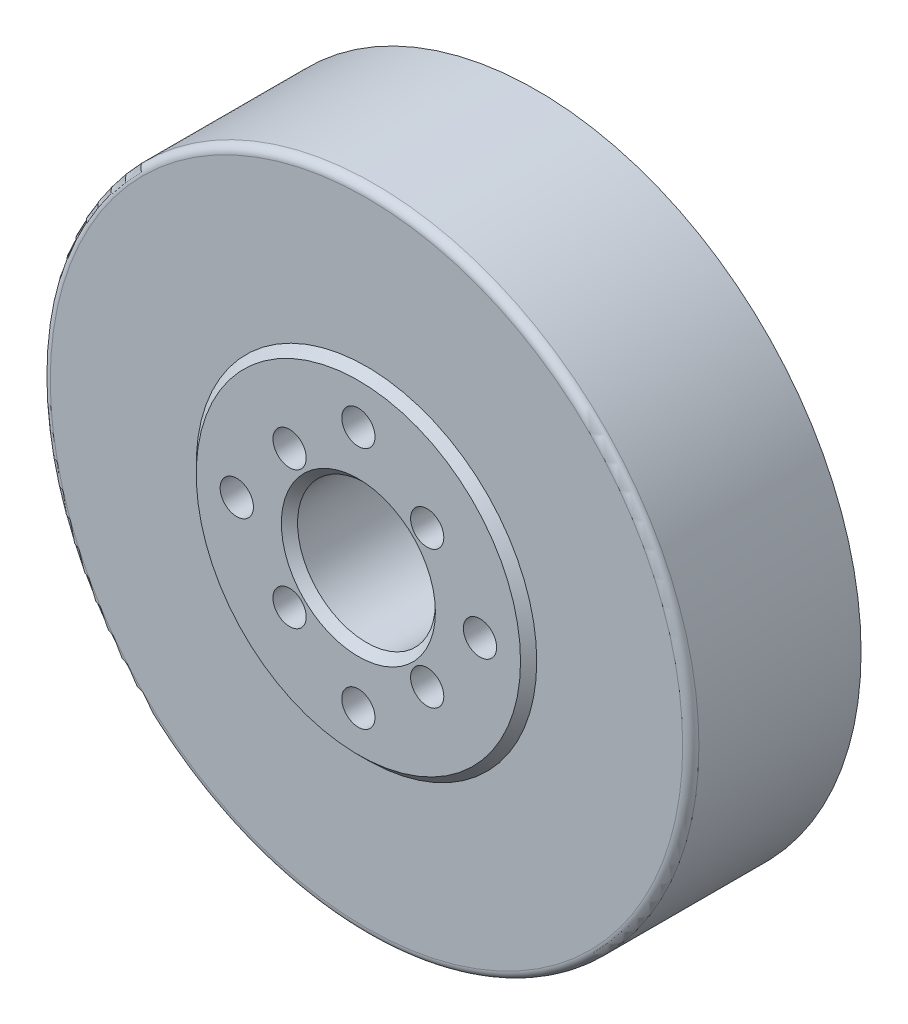
SolidWorks part; units mm, degrees
ref_plane "Front Plane" through (0, 0, 0) normal (1, 0, 0) x (0, 1, 0)
ref_plane "Top Plane" through (0, 0, 0) normal (0, 0, 1) x (0, 1, 0)
ref_plane "Right Plane" through (0, 0, 0) normal (0, 1, 0) x (-1, 0, 0)
sketch "Sketch1" plane through (0, 0, 0) normal (0, 0, 1) x (0, 1, 0)
  circle A0 centre (0, 0) radius 20
  dimension "D1" = 40
extrude "Boss-Extrude1" add sketch "Sketch1" along normal blind 10.5
sketch "Sketch2" plane through (0, 0, 10.5) normal (0, 0, 1) x (1, 0, 0)
  circle A0 centre (0, 0) radius 4.25
  circle A1 centre (0, 0) radius 10.5
  dimension "D1" = 8.5
  dimension "D2" = 21
extrude "Boss-Extrude3" add sketch "Sketch2" along normal blind 0.5 draft 45
sketch "Sketch3" plane through (0, 0, 10.5) normal (0, 0, 1) x (1, 0, 0)
  circle A0 centre (0, 0) radius 4.25
  circle A1 centre (0, 0) radius 4.25 construction
extrude "Cut-Extrude1" cut sketch "Sketch3" against normal blind 10.5
sketch "Sketch10" plane through (0, 0, 11) normal (0, 0, 1) x (0, -1, 0)
  line L1 (-7.5, 0) -> (0, -7.5) construction
  line L2 (0, -7.5) -> (7.5, 0) construction
  line L3 (7.5, 0) -> (0, 7.5) construction
  line L4 (0, 7.5) -> (-7.5, 0) construction
  line L5 (4.2426, 4.2426) -> (-4.2426, 4.2426) construction
  line L6 (-4.2426, 4.2426) -> (-4.2426, -4.2426) construction
  line L7 (-4.2426, -4.2426) -> (4.2426, -4.2426) construction
  line L8 (4.2426, -4.2426) -> (4.2426, 4.2426) construction
  circle A0 centre (0, 0) radius 7.5 construction
  circle A1 centre (0, 0) radius 6 construction
  point P2 (-7.5, 0)
  point P3 (0, -7.5)
  point P4 (7.5, 0)
  point P5 (0, 7.5)
  point P9 (4.2426, 4.2426)
  point P10 (-4.2426, 4.2426)
  point P11 (-4.2426, -4.2426)
  point P12 (4.2426, -4.2426)
  dimension "D1" = 15
  dimension "D2" = 12
hole_wizard "M2.5x0.45 Tapped Hole1" positions "Sketch10" profile "Sketch12" tap size "M2.5x0.45" standard "ANSI Metric"
sketch "Sketch12" plane through (-4.2426, -4.2426, 11) normal (1, 0, 0) x (0, -1, 0)
  line L0 (0, 0) -> (0, 5)
  line L1 (0, 5) -> (1.025, 4.3841)
  line L2 (1.025, 4.3841) -> (1.025, 0)
  line L5 (1.025, 0) -> (0, 0)
  line L10 (0, 5) -> (-1.025, 4.3841) construction
  line L11 (0, -6.35) -> (0, 107.95) construction
  dimension "Tap Drill Dia." = 2.05
  dimension "Tap Drill Depth" = 5
  dimension "Drill Angle" = 118
cosmetic thread "Hole Thread1" parameters "D1"=5, "D2"=2.5
cosmetic thread "Hole Thread2" parameters "D1"=5, "D2"=2.5
cosmetic thread "Hole Thread3" parameters "D1"=5, "D2"=2.5
cosmetic thread "Hole Thread4" parameters "D1"=5, "D2"=2.5
cosmetic thread "Hole Thread5" parameters "D1"=5, "D2"=2.5
cosmetic thread "Hole Thread6" parameters "D1"=5, "D2"=2.5
cosmetic thread "Hole Thread7" parameters "D1"=5, "D2"=2.5
cosmetic thread "Hole Thread8" parameters "D1"=5, "D2"=2.5
fillet "Fillet1" radius 0.5 1 edges at (20, 0, 10.5)
